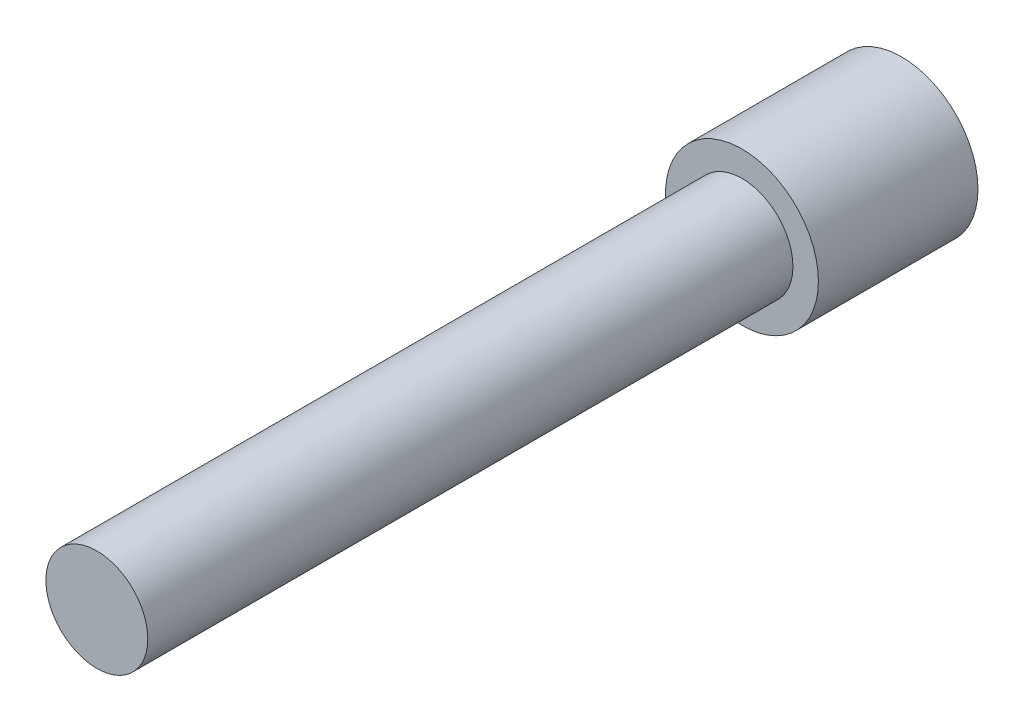
SolidWorks part; units mm, degrees
material "Aluminum"
ref_plane "Front Plane" through (0, 0, 0) normal (0, 0, 1) x (1, 0, 0)
ref_plane "Top Plane" through (0, 0, 0) normal (0, 1, 0) x (1, 0, 0)
ref_plane "Right Plane" through (0, 0, 0) normal (1, 0, 0) x (0, 0, -1)
sketch "Sketch1" plane through (0, 0, 0) normal (0, 0, 1) x (1, 0, 0)
  circle A0 centre (0, 0) radius 2.25
  dimension "D1" = 4.5
extrude "Boss-Extrude1" add sketch "Sketch1" along normal blind 4.7
sketch "Sketch2" plane through (0, 0, 4.7) normal (0, 0, 1) x (1, 0, 0)
  circle A0 centre (0, 0) radius 1.5
  dimension "D1" = 3
extrude "Boss-Extrude2" add sketch "Sketch2" along normal blind 19
sketch "Sketch3" plane through (0, 0, 0) normal (0, 0, -1) x (-1, 0, 0)
  circle A0 centre (0, 0) radius 1.5
  dimension "D1" = 3
extrude "Cut-Extrude1" cut sketch "Sketch3" against normal blind 3
